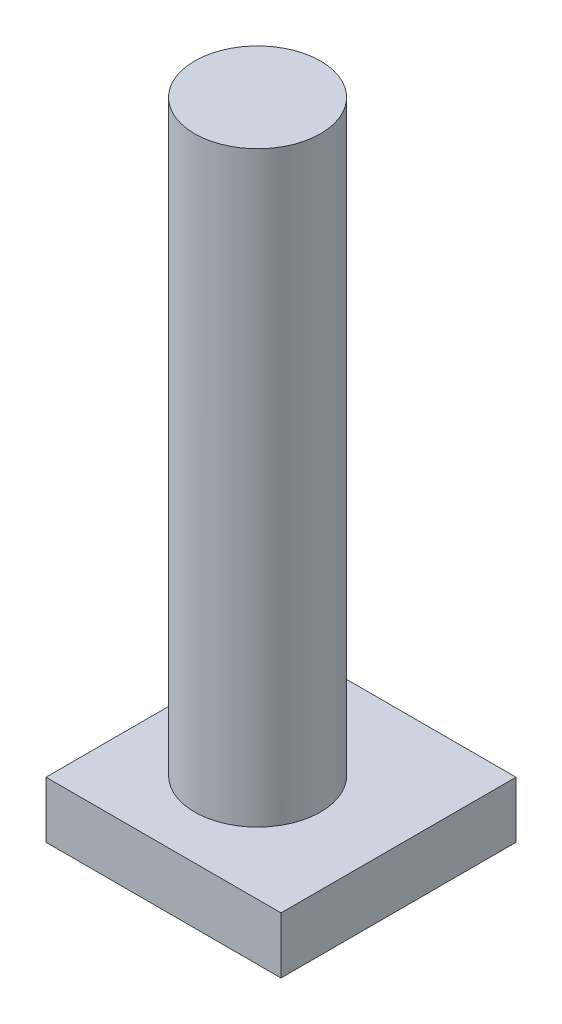
SolidWorks part; units mm, degrees
ref_plane "Front Plane" through (0, 0, 0) normal (0, 0, 1) x (1, 0, 0)
ref_plane "Top Plane" through (0, 0, 0) normal (0, 1, 0) x (1, 0, 0)
ref_plane "Right Plane" through (0, 0, 0) normal (1, 0, 0) x (0, 0, -1)
sketch "Sketch1" plane through (0, 0, 0) normal (0, 1, 0) x (1, 0, 0)
  line L1 (0, 0) -> (25.4, 0)
  line L2 (0, 0) -> (0, 25.4)
  line L3 (0, 25.4) -> (25.4, 25.4)
  line L4 (25.4, 0) -> (25.4, 25.4)
  dimension "D1" = 25.4
extrude "Boss-Extrude1" add sketch "Sketch1" along normal blind 6.096
sketch "Sketch2" plane through (0, 6.096, 0) normal (0, 1, 0) x (1, 0, 0)
  circle A0 centre (11.2927, 11.5758) radius 6.8092
extrude "Boss-Extrude2" add sketch "Sketch2" along normal blind 63.5
